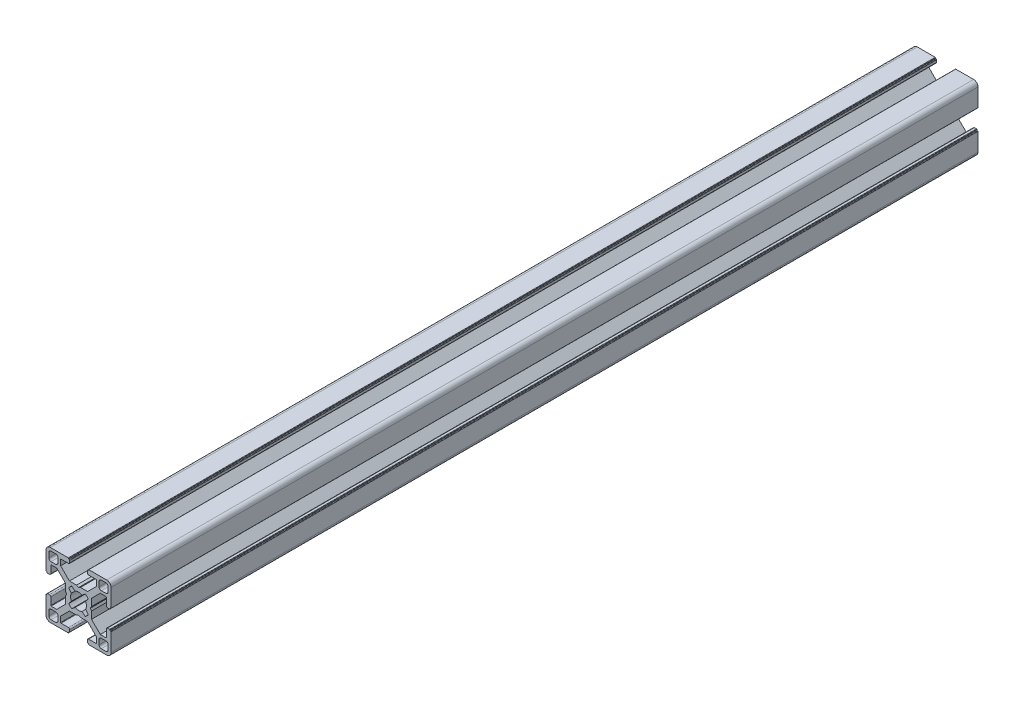
SolidWorks part; units mm, degrees
ref_plane "Front" through (0, 0, 0) normal (0, 0, 1) x (1, 0, 0)
ref_plane "Top" through (0, 0, 0) normal (0, 1, 0) x (1, 0, 0)
ref_plane "Right" through (0, 0, 0) normal (1, 0, 0) x (0, 0, -1)
sketch "Sketch1" plane through (0, 0, 0) normal (0, 0, 1) x (1, 0, 0)
  line L0 (13.7, 12.7) -> (13.7, 10.5)
  line L1 (10.5, 9.5) -> (12.7, 9.5)
  line L2 (9.5, 12.7) -> (9.5, 10.5)
  line L3 (10.5, 13.7) -> (12.7, 13.7)
  line L4 (3.1359, 4.5184) -> (1.6001, 3.2806)
  line L5 (3.2806, 1.6001) -> (4.5053, 3.1547)
  line L6 (6.0045, 0.9) -> (5.4849, 0)
  line L7 (6.0045, 4.2045) -> (6.0045, 0.9)
  line L8 (0, -5.4849) -> (0.9, -6)
  line L9 (0.9, -6) -> (4.2045, -6)
  line L10 (4.2045, -6) -> (8.25, -10.05)
  line L11 (8.25, -10.05) -> (8.25, -12.6)
  line L12 (4.65, -12.8) -> (8.05, -12.8)
  line L13 (4.05, -14.3) -> (4.05, -13.4)
  line L14 (4.25, -14.5) -> (4.35, -14.5)
  line L15 (4.55, -14.8) -> (4.55, -14.7)
  line L16 (4.75, -15) -> (13, -15)
  line L17 (15, -13) -> (15, -4.75)
  line L18 (14.7, -4.55) -> (14.8, -4.55)
  line L19 (14.5, -4.35) -> (14.5, -4.25)
  line L20 (13.4, -4.05) -> (14.3, -4.05)
  line L21 (12.8, -8.05) -> (12.8, -4.65)
  line L22 (12.6, -8.25) -> (10.05, -8.25)
  line L23 (10.05, -8.25) -> (6.0045, -4.2045)
  line L24 (6.0045, -4.2045) -> (6.0045, -0.9)
  line L25 (6.0045, -0.9) -> (5.4849, 0)
  line L26 (10.05, 8.25) -> (6.0045, 4.2045)
  line L27 (12.6, 8.25) -> (10.05, 8.25)
  line L28 (12.8, 8.05) -> (12.8, 4.65)
  line L29 (13.4, 4.05) -> (14.3, 4.05)
  line L30 (14.5, 4.35) -> (14.5, 4.25)
  line L31 (14.7, 4.55) -> (14.8, 4.55)
  line L32 (15, 13) -> (15, 4.75)
  line L33 (4.75, 15) -> (13, 15)
  line L34 (4.55, 14.8) -> (4.55, 14.7)
  line L35 (4.25, 14.5) -> (4.35, 14.5)
  line L36 (4.05, 14.3) -> (4.05, 13.4)
  line L37 (4.65, 12.8) -> (8.05, 12.8)
  line L38 (8.25, 10.05) -> (8.25, 12.6)
  line L39 (4.2045, 6) -> (8.25, 10.05)
  line L40 (0.9, 6) -> (4.2045, 6)
  line L41 (0, 5.4849) -> (0.9, 6)
  line L42 (-13.7, -12.7) -> (-13.7, -10.5)
  line L43 (-10.5, -9.5) -> (-12.7, -9.5)
  line L44 (-9.5, -12.7) -> (-9.5, -10.5)
  line L45 (-10.5, -13.7) -> (-12.7, -13.7)
  line L46 (-3.1359, -4.5184) -> (-1.6001, -3.2806)
  line L47 (-3.2806, -1.6001) -> (-4.5053, -3.1547)
  line L48 (0, 5.4849) -> (-0.9, 6)
  line L49 (-0.9, 6) -> (-4.2045, 6)
  line L50 (-4.2045, 6) -> (-8.25, 10.05)
  line L51 (-8.25, 10.05) -> (-8.25, 12.6)
  line L52 (-4.65, 12.8) -> (-8.05, 12.8)
  line L53 (-4.05, 14.3) -> (-4.05, 13.4)
  line L54 (-4.25, 14.5) -> (-4.35, 14.5)
  line L55 (-4.55, 14.8) -> (-4.55, 14.7)
  line L56 (-4.75, 15) -> (-13, 15)
  line L57 (-15, 13) -> (-15, 4.75)
  line L58 (-14.7, 4.55) -> (-14.8, 4.55)
  line L59 (-14.5, 4.35) -> (-14.5, 4.25)
  line L60 (-13.4, 4.05) -> (-14.3, 4.05)
  line L61 (-12.8, 8.05) -> (-12.8, 4.65)
  line L62 (-12.6, 8.25) -> (-10.05, 8.25)
  line L63 (-10.05, 8.25) -> (-6.0045, 4.2045)
  line L64 (-6.0045, -0.9) -> (-5.4849, 0)
  line L65 (-6.0045, -4.2045) -> (-6.0045, -0.9)
  line L66 (-10.05, -8.25) -> (-6.0045, -4.2045)
  line L67 (-12.6, -8.25) -> (-10.05, -8.25)
  line L68 (-12.8, -8.05) -> (-12.8, -4.65)
  line L69 (-13.4, -4.05) -> (-14.3, -4.05)
  line L70 (-14.5, -4.35) -> (-14.5, -4.25)
  line L71 (-14.7, -4.55) -> (-14.8, -4.55)
  line L72 (-15, -13) -> (-15, -4.75)
  line L73 (-4.75, -15) -> (-13, -15)
  line L74 (-4.55, -14.8) -> (-4.55, -14.7)
  line L75 (-4.25, -14.5) -> (-4.35, -14.5)
  line L76 (-4.05, -14.3) -> (-4.05, -13.4)
  line L77 (3.2806, -1.6001) -> (4.5053, -3.1547)
  line L78 (3.1359, -4.5184) -> (1.6001, -3.2806)
  line L79 (-4.65, -12.8) -> (-8.05, -12.8)
  line L80 (-8.25, -10.05) -> (-8.25, -12.6)
  line L81 (-4.2045, -6) -> (-8.25, -10.05)
  line L82 (-0.9, -6) -> (-4.2045, -6)
  line L83 (0, -5.4849) -> (-0.9, -6)
  line L84 (10.5, -13.7) -> (12.7, -13.7)
  line L85 (9.5, -12.7) -> (9.5, -10.5)
  line L86 (10.5, -9.5) -> (12.7, -9.5)
  line L87 (13.7, -12.7) -> (13.7, -10.5)
  line L88 (-6.0045, 4.2045) -> (-6.0045, 0.9)
  line L89 (-6.0045, 0.9) -> (-5.4849, 0)
  line L90 (-3.2806, 1.6001) -> (-4.5053, 3.1547)
  line L91 (-3.1359, 4.5184) -> (-1.6001, 3.2806)
  line L92 (-10.5, 13.7) -> (-12.7, 13.7)
  line L93 (-9.5, 12.7) -> (-9.5, 10.5)
  line L94 (-10.5, 9.5) -> (-12.7, 9.5)
  line L95 (-13.7, 12.7) -> (-13.7, 10.5)
  line L96 (-23.4857, 0) -> (20.9308, 0) construction
  line L97 (0, 17.9563) -> (0, -17.361) construction
  arc A0 (13.7, 12.7) -> (12.7, 13.7) centre (12.7, 12.7) ccw
  arc A1 (12.7, 9.5) -> (13.7, 10.5) centre (12.7, 10.5) ccw
  arc A2 (9.5, 10.5) -> (10.5, 9.5) centre (10.5, 10.5) ccw
  arc A3 (10.5, 13.7) -> (9.5, 12.7) centre (10.5, 12.7) ccw
  arc A4 (1.6001, 3.2806) -> (-1.6001, 3.2806) centre (0, 0) ccw
  arc A5 (8.25, -12.6) -> (8.05, -12.8) centre (8.05, -12.6) cw
  arc A6 (4.65, -12.8) -> (4.05, -13.4) centre (4.65, -13.4) ccw
  arc A7 (4.05, -14.3) -> (4.25, -14.5) centre (4.25, -14.3) ccw
  arc A8 (4.35, -14.5) -> (4.55, -14.7) centre (4.35, -14.7) cw
  arc A9 (4.55, -14.8) -> (4.75, -15) centre (4.75, -14.8) ccw
  arc A10 (13, -15) -> (15, -13) centre (13, -13) ccw
  arc A11 (15, -4.75) -> (14.8, -4.55) centre (14.8, -4.75) ccw
  arc A12 (14.7, -4.55) -> (14.5, -4.35) centre (14.7, -4.35) cw
  arc A13 (14.5, -4.25) -> (14.3, -4.05) centre (14.3, -4.25) ccw
  arc A14 (13.4, -4.05) -> (12.8, -4.65) centre (13.4, -4.65) ccw
  arc A15 (12.8, -8.05) -> (12.6, -8.25) centre (12.6, -8.05) cw
  arc A16 (4.5053, 3.1547) -> (3.1359, 4.5184) centre (0, 0) ccw
  arc A17 (12.8, 8.05) -> (12.6, 8.25) centre (12.6, 8.05) ccw
  arc A18 (13.4, 4.05) -> (12.8, 4.65) centre (13.4, 4.65) cw
  arc A19 (14.5, 4.25) -> (14.3, 4.05) centre (14.3, 4.25) cw
  arc A20 (14.7, 4.55) -> (14.5, 4.35) centre (14.7, 4.35) ccw
  arc A21 (15, 4.75) -> (14.8, 4.55) centre (14.8, 4.75) cw
  arc A22 (13, 15) -> (15, 13) centre (13, 13) cw
  arc A23 (4.55, 14.8) -> (4.75, 15) centre (4.75, 14.8) cw
  arc A24 (4.35, 14.5) -> (4.55, 14.7) centre (4.35, 14.7) ccw
  arc A25 (4.05, 14.3) -> (4.25, 14.5) centre (4.25, 14.3) cw
  arc A26 (4.65, 12.8) -> (4.05, 13.4) centre (4.65, 13.4) cw
  arc A27 (8.25, 12.6) -> (8.05, 12.8) centre (8.05, 12.6) ccw
  arc A28 (-13.7, -12.7) -> (-12.7, -13.7) centre (-12.7, -12.7) ccw
  arc A29 (-12.7, -9.5) -> (-13.7, -10.5) centre (-12.7, -10.5) ccw
  arc A30 (-9.5, -10.5) -> (-10.5, -9.5) centre (-10.5, -10.5) ccw
  arc A31 (-10.5, -13.7) -> (-9.5, -12.7) centre (-10.5, -12.7) ccw
  arc A32 (-4.5053, -3.1547) -> (-3.1359, -4.5184) centre (0, 0) ccw
  arc A33 (-3.2806, 1.6001) -> (-3.2806, -1.6001) centre (0, 0) ccw
  arc A34 (-8.25, 12.6) -> (-8.05, 12.8) centre (-8.05, 12.6) cw
  arc A35 (-4.65, 12.8) -> (-4.05, 13.4) centre (-4.65, 13.4) ccw
  arc A36 (-4.05, 14.3) -> (-4.25, 14.5) centre (-4.25, 14.3) ccw
  arc A37 (-4.35, 14.5) -> (-4.55, 14.7) centre (-4.35, 14.7) cw
  arc A38 (-4.55, 14.8) -> (-4.75, 15) centre (-4.75, 14.8) ccw
  arc A39 (-13, 15) -> (-15, 13) centre (-13, 13) ccw
  arc A40 (-15, 4.75) -> (-14.8, 4.55) centre (-14.8, 4.75) ccw
  arc A41 (-14.7, 4.55) -> (-14.5, 4.35) centre (-14.7, 4.35) cw
  arc A42 (-14.5, 4.25) -> (-14.3, 4.05) centre (-14.3, 4.25) ccw
  arc A43 (-13.4, 4.05) -> (-12.8, 4.65) centre (-13.4, 4.65) ccw
  arc A44 (-12.8, 8.05) -> (-12.6, 8.25) centre (-12.6, 8.05) cw
  arc A45 (-4.5053, 3.1547) -> (-3.1359, 4.5184) centre (0, 0) cw
  arc A46 (-12.8, -8.05) -> (-12.6, -8.25) centre (-12.6, -8.05) ccw
  arc A47 (-13.4, -4.05) -> (-12.8, -4.65) centre (-13.4, -4.65) cw
  arc A48 (-14.5, -4.25) -> (-14.3, -4.05) centre (-14.3, -4.25) cw
  arc A49 (3.2806, 1.6001) -> (3.2806, -1.6001) centre (0, 0) cw
  arc A50 (4.5053, -3.1547) -> (3.1359, -4.5184) centre (0, 0) cw
  arc A51 (1.6001, -3.2806) -> (-1.6001, -3.2806) centre (0, 0) cw
  arc A52 (-14.7, -4.55) -> (-14.5, -4.35) centre (-14.7, -4.35) ccw
  arc A53 (-15, -4.75) -> (-14.8, -4.55) centre (-14.8, -4.75) cw
  arc A54 (-13, -15) -> (-15, -13) centre (-13, -13) cw
  arc A55 (-4.55, -14.8) -> (-4.75, -15) centre (-4.75, -14.8) cw
  arc A56 (10.5, -13.7) -> (9.5, -12.7) centre (10.5, -12.7) cw
  arc A57 (9.5, -10.5) -> (10.5, -9.5) centre (10.5, -10.5) cw
  arc A58 (12.7, -9.5) -> (13.7, -10.5) centre (12.7, -10.5) cw
  arc A59 (13.7, -12.7) -> (12.7, -13.7) centre (12.7, -12.7) cw
  arc A60 (-4.35, -14.5) -> (-4.55, -14.7) centre (-4.35, -14.7) ccw
  arc A61 (-4.05, -14.3) -> (-4.25, -14.5) centre (-4.25, -14.3) cw
  arc A62 (-4.65, -12.8) -> (-4.05, -13.4) centre (-4.65, -13.4) cw
  arc A63 (-8.25, -12.6) -> (-8.05, -12.8) centre (-8.05, -12.6) ccw
  arc A64 (-10.5, 13.7) -> (-9.5, 12.7) centre (-10.5, 12.7) cw
  arc A65 (-9.5, 10.5) -> (-10.5, 9.5) centre (-10.5, 10.5) cw
  arc A66 (-12.7, 9.5) -> (-13.7, 10.5) centre (-12.7, 10.5) cw
  arc A67 (-13.7, 12.7) -> (-12.7, 13.7) centre (-12.7, 12.7) cw
  point P81 (15, 15)
  point P82 (0, 15)
  point P203 (0, -15)
  point P204 (15, -15)
  point P206 (0, 0)
  point P207 (15, 0)
  point P219 (-15, 0)
  point P220 (-15, -15)
  point P221 (-15, 15)
  dimension "D6" = 7.3
  dimension "D7" = 11
  dimension "D1" = 30
  dimension "D2" = 15
  dimension "D3" = 30
  dimension "D4" = 8.1
  dimension "D5" = 9
  dimension "D8" = 8.1
extrude "Base-Extrude" add sketch "Sketch1" against normal blind 400
